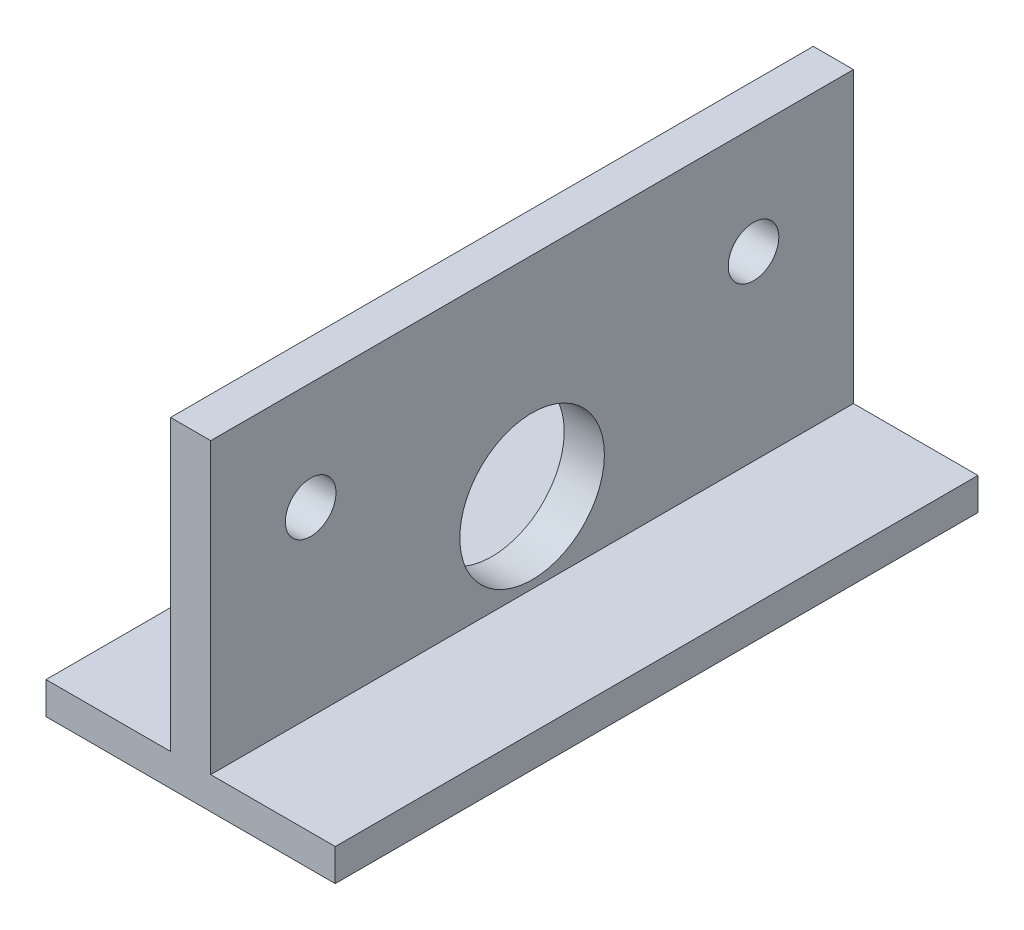
SolidWorks part; units mm, degrees
ref_plane "Front Plane" through (0, 0, 0) normal (0, 0, 1) x (1, 0, 0)
ref_plane "Top Plane" through (0, 0, 0) normal (0, 1, 0) x (1, 0, 0)
ref_plane "Right Plane" through (0, 0, 0) normal (1, 0, 0) x (0, 0, -1)
sketch "Sketch3" plane through (0, 0, 0) normal (1, 0, 0) x (0, 0, -1)
  line L0 (17.5006, 4.191) -> (-17.5006, 4.191) construction
  line L1 (-25.4, -12.7) -> (25.4, -12.7)
  line L2 (-25.4, -12.7) -> (-25.4, 12.7)
  line L3 (-25.4, 12.7) -> (25.4, 12.7)
  line L4 (25.4, -12.7) -> (25.4, 12.7)
  line L5 (-25.4, -12.7) -> (25.4, 12.7) construction
  line L6 (-25.4, 12.7) -> (25.4, -12.7) construction
  line L7 (0, 0) -> (0, 4.191) construction
  circle A0 centre (-17.5006, 4.191) radius 2.0003
  circle A1 centre (17.5006, 4.191) radius 2.0002
  circle A3 centre (0, -3.81) radius 5.715
  point P0 (0, 0)
  point P14 (0, 0)
  dimension "D2" = 35.0012
  dimension "D3" = 4.0005
  dimension "D4" = 16.891
  dimension "D6" = 8.001
  dimension "D7" = 11.43
  dimension "D1" = 50.8
  dimension "D5" = 25.4
extrude "Boss-Extrude1" add sketch "Sketch3" along normal mid plane 3.175
sketch "Sketch4" plane through (0, 0, 0) normal (1, 0, 0) x (0, 0, -1)
  line L0 (-25.4, 12.7) -> (-25.4, -12.7) construction
  line L1 (-25.4, -10.16) -> (25.4, -10.16)
  line L2 (-25.4, -10.16) -> (-25.4, -12.7)
  line L3 (-25.4, -12.7) -> (25.4, -12.7)
  line L4 (25.4, -10.16) -> (25.4, -12.7)
  line L5 (-25.4, -10.16) -> (25.4, -12.7) construction
  line L6 (-25.4, -12.7) -> (25.4, -10.16) construction
  point P0 (0, -11.43)
  point P5 (-25.4, -6.0278)
  dimension "D1" = 2.54
extrude "Boss-Extrude2" add sketch "Sketch4" along normal mid plane 22.86
